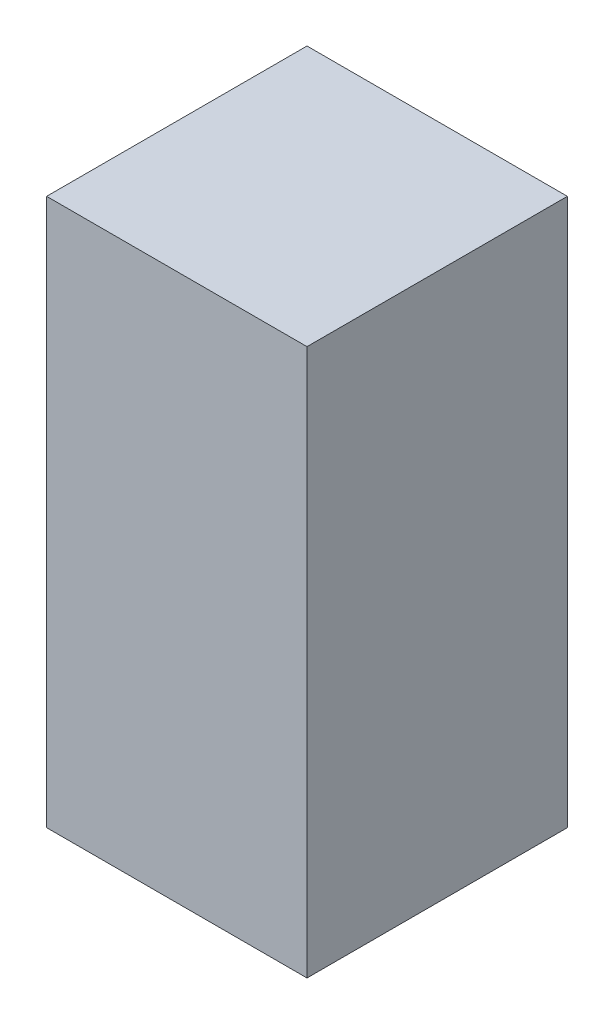
SolidWorks part; units mm, degrees
ref_plane "Front Plane" through (0, 0, 0) normal (0, 0, 1) x (1, 0, 0)
ref_plane "Top Plane" through (0, 0, 0) normal (0, 1, 0) x (1, 0, 0)
ref_plane "Right Plane" through (0, 0, 0) normal (1, 0, 0) x (0, 0, -1)
sketch "Sketch1" plane through (0, 0, 0) normal (0, 0, 1) x (1, 0, 0)
  line L1 (0, 0) -> (100, 0)
  line L2 (0, 0) -> (0, 210)
  line L3 (0, 210) -> (100, 210)
  line L4 (100, 0) -> (100, 210)
  dimension "D1" = 100
  dimension "D2" = 210
extrude "Boss-Extrude1" add sketch "Sketch1" along normal blind 100
fillet "Fillet1" [suppressed] radius 20
sketch "Sketch2" plane through (0, 0, 0) normal (1, 0, 0) x (0, 0, -1)
  line L0 (-50, 210) -> (-50, 0) construction
  line L1 (-100, 210) -> (0, 210) construction
  line L2 (55, 0) -> (-55, 0) construction
  circle A0 centre (-50, 154.385) radius 45
  circle A1 centre (-50, 55.015) radius 45
  dimension "D1" = 90
  dimension "D2" = 99.37
  dimension "D3" = 55.615
